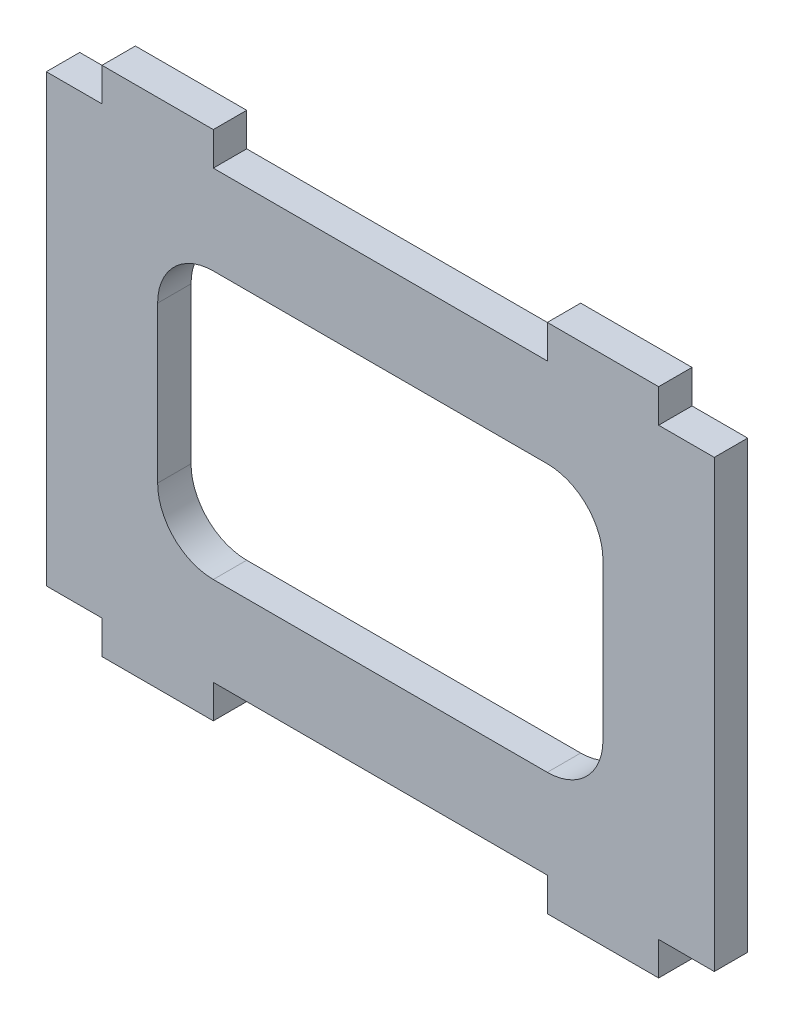
SolidWorks part; units mm, degrees
ref_plane "Plan de face" through (0, 0, 0) normal (0, 0, 1) x (1, 0, 0)
ref_plane "Plan de dessus" through (0, 0, 0) normal (0, 1, 0) x (1, 0, 0)
ref_plane "Plan de droite" through (0, 0, 0) normal (1, 0, 0) x (0, 0, -1)
sketch "Esquisse1" plane through (0, 0, 0) normal (0, 0, 1) x (1, 0, 0)
  line L0 (-5, -25) -> (-5, -28)
  line L1 (-10, 15) -> (-5, 15)
  line L2 (-10, 15) -> (-10, -25)
  line L3 (-10, -25) -> (-5, -25)
  line L4 (20, 15) -> (20, -25)
  line L5 (5, -25) -> (20, -25)
  line L7 (-5, 18) -> (5, 18)
  line L8 (-5, 18) -> (-5, 15)
  line L9 (-5, -28) -> (5, -28)
  line L10 (5, 18) -> (5, 15)
  line L15 (5, -25) -> (5, -28)
  line L16 (5, 15) -> (20, 15)
  point P0 (0, 0)
  point P6 (0, 0)
  dimension "D1" = 30
  dimension "D2" = 40
  dimension "D3" = 10
  dimension "D4" = 3
  dimension "D5" = 3
  dimension "D6" = 5
extrude "Boss.-Extru.1" add sketch "Esquisse1" along normal blind 3
mirror "Symétrie1" about plane through (20, 15, 3) normal (-1, 0, 0) of bodies 101
sketch "Esquisse2" plane through (0, 0, 3) normal (0, 0, 1) x (1, 0, 0)
  line L0 (35, 15) -> (5, 15) construction
  line L1 (5, 7) -> (35, 7)
  line L2 (0, 2) -> (0, -12)
  line L3 (5, -17) -> (35, -17)
  line L4 (40, 2) -> (40, -12)
  line L5 (5, -25) -> (35, -25) construction
  line L6 (-10, 15) -> (-10, -25) construction
  line L7 (50, 15) -> (50, -25) construction
  arc A0 (35, 7) -> (40, 2) centre (35, 2) cw
  arc A1 (35, -17) -> (40, -12) centre (35, -12) ccw
  arc A2 (0, -12) -> (5, -17) centre (5, -12) ccw
  arc A3 (5, 7) -> (0, 2) centre (5, 2) ccw
  dimension "D5" = 5
  dimension "D1" = 8
  dimension "D2" = 8
  dimension "D3" = 10
  dimension "D4" = 10
extrude "Enlèv. mat.-Extru.1" cut sketch "Esquisse2" against normal through all
